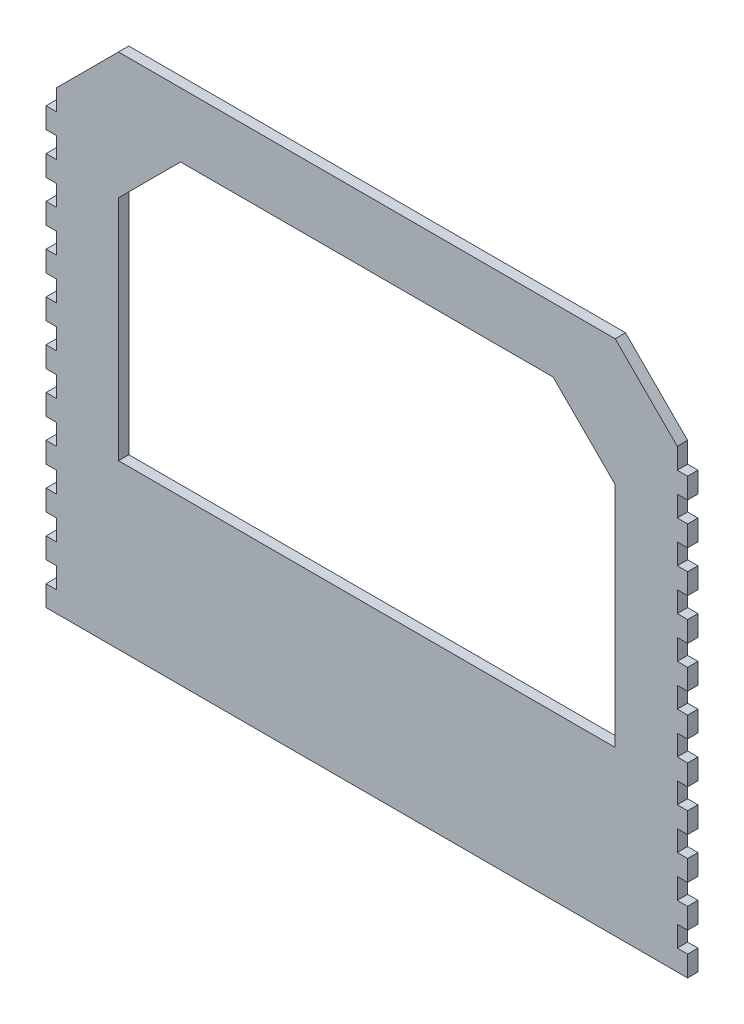
SolidWorks part; units mm, degrees
material "Buche"
ref_plane "Ebene vorne" through (0, 0, 0) normal (0, 0, 1) x (1, 0, 0)
ref_plane "Ebene oben" through (0, 0, 0) normal (0, 1, 0) x (1, 0, 0)
ref_plane "Ebene rechts" through (0, 0, 0) normal (1, 0, 0) x (0, 0, -1)
sketch "Skizze1" plane through (0, 0, 0) normal (0, 0, 1) x (1, 0, 0)
  line L0 (430.8962, 326.3402) -> (430.8962, 336.3402)
  line L1 (430.8962, 316.3402) -> (730.8962, 316.3402)
  line L2 (730.8962, 326.3402) -> (730.8962, 336.3402)
  line L3 (460.8962, 566.3402) -> (700.8962, 566.3402)
  line L4 (430.8962, 536.3402) -> (460.8962, 566.3402)
  line L5 (730.8962, 536.3402) -> (700.8962, 566.3402)
  line L6 (700.8962, 505.3114) -> (670.8962, 535.3114)
  line L7 (460.8962, 395.3114) -> (700.8962, 395.3114)
  line L8 (460.8962, 395.3114) -> (460.8962, 505.3114)
  line L9 (490.8962, 535.3114) -> (670.8962, 535.3114)
  line L10 (700.8962, 395.3114) -> (700.8962, 505.3114)
  line L11 (460.8962, 505.3114) -> (490.8962, 535.3114)
  line L13 (730.8962, 316.3402) -> (735.8962, 316.3402)
  line L14 (735.8962, 316.3402) -> (735.8962, 326.3402)
  line L15 (735.8962, 326.3402) -> (730.8962, 326.3402)
  line L16 (730.8962, 346.3402) -> (730.8962, 356.3402)
  line L17 (730.8962, 336.3402) -> (735.8962, 336.3402)
  line L18 (735.8962, 336.3402) -> (735.8962, 346.3402)
  line L19 (735.8962, 346.3402) -> (730.8962, 346.3402)
  line L20 (730.8962, 366.3402) -> (730.8962, 376.3402)
  line L21 (730.8962, 356.3402) -> (735.8962, 356.3402)
  line L22 (735.8962, 356.3402) -> (735.8962, 366.3402)
  line L23 (735.8962, 366.3402) -> (730.8962, 366.3402)
  line L24 (730.8962, 386.3402) -> (730.8962, 396.3402)
  line L25 (730.8962, 376.3402) -> (735.8962, 376.3402)
  line L26 (735.8962, 376.3402) -> (735.8962, 386.3402)
  line L27 (735.8962, 386.3402) -> (730.8962, 386.3402)
  line L28 (730.8962, 406.3402) -> (730.8962, 416.3402)
  line L29 (730.8962, 396.3402) -> (735.8962, 396.3402)
  line L30 (735.8962, 396.3402) -> (735.8962, 406.3402)
  line L31 (735.8962, 406.3402) -> (730.8962, 406.3402)
  line L32 (730.8962, 426.3402) -> (730.8962, 436.3402)
  line L33 (730.8962, 416.3402) -> (735.8962, 416.3402)
  line L34 (735.8962, 416.3402) -> (735.8962, 426.3402)
  line L35 (735.8962, 426.3402) -> (730.8962, 426.3402)
  line L36 (730.8962, 446.3402) -> (730.8962, 456.3402)
  line L37 (730.8962, 436.3402) -> (735.8962, 436.3402)
  line L38 (735.8962, 436.3402) -> (735.8962, 446.3402)
  line L39 (735.8962, 446.3402) -> (730.8962, 446.3402)
  line L40 (730.8962, 466.3402) -> (730.8962, 476.3402)
  line L41 (730.8962, 456.3402) -> (735.8962, 456.3402)
  line L42 (735.8962, 456.3402) -> (735.8962, 466.3402)
  line L43 (735.8962, 466.3402) -> (730.8962, 466.3402)
  line L44 (730.8962, 486.3402) -> (730.8962, 496.3402)
  line L45 (730.8962, 476.3402) -> (735.8962, 476.3402)
  line L46 (735.8962, 476.3402) -> (735.8962, 486.3402)
  line L47 (735.8962, 486.3402) -> (730.8962, 486.3402)
  line L48 (730.8962, 506.3402) -> (730.8962, 516.3402)
  line L49 (730.8962, 496.3402) -> (735.8962, 496.3402)
  line L50 (735.8962, 496.3402) -> (735.8962, 506.3402)
  line L51 (735.8962, 506.3402) -> (730.8962, 506.3402)
  line L52 (730.8962, 526.3402) -> (730.8962, 536.3402)
  line L53 (730.8962, 516.3402) -> (735.8962, 516.3402)
  line L54 (735.8962, 516.3402) -> (735.8962, 526.3402)
  line L55 (735.8962, 526.3402) -> (730.8962, 526.3402)
  line L56 (430.8962, 316.3402) -> (425.8962, 316.3402)
  line L57 (425.8962, 316.3402) -> (425.8962, 326.3402)
  line L58 (425.8962, 326.3402) -> (430.8962, 326.3402)
  line L59 (430.8962, 346.3402) -> (430.8962, 356.3402)
  line L60 (425.8962, 336.3402) -> (425.8962, 346.3402)
  line L61 (425.8962, 346.3402) -> (430.8962, 346.3402)
  line L62 (430.8962, 366.3402) -> (430.8962, 376.3402)
  line L63 (425.8962, 356.3402) -> (425.8962, 366.3402)
  line L64 (425.8962, 366.3402) -> (430.8962, 366.3402)
  line L65 (430.8962, 386.3402) -> (430.8962, 396.3402)
  line L66 (425.8962, 376.3402) -> (425.8962, 386.3402)
  line L67 (425.8962, 386.3402) -> (430.8962, 386.3402)
  line L68 (430.8962, 406.3402) -> (430.8962, 416.3402)
  line L69 (425.8962, 396.3402) -> (425.8962, 406.3402)
  line L70 (425.8962, 406.3402) -> (430.8962, 406.3402)
  line L71 (430.8962, 426.3402) -> (430.8962, 436.3402)
  line L72 (425.8962, 416.3402) -> (425.8962, 426.3402)
  line L73 (425.8962, 426.3402) -> (430.8962, 426.3402)
  line L74 (430.8962, 446.3402) -> (430.8962, 456.3402)
  line L75 (425.8962, 436.3402) -> (425.8962, 446.3402)
  line L76 (425.8962, 446.3402) -> (430.8962, 446.3402)
  line L77 (430.8962, 466.3402) -> (430.8962, 476.3402)
  line L78 (425.8962, 456.3402) -> (425.8962, 466.3402)
  line L79 (425.8962, 466.3402) -> (430.8962, 466.3402)
  line L80 (430.8962, 486.3402) -> (430.8962, 496.3402)
  line L81 (425.8962, 476.3402) -> (425.8962, 486.3402)
  line L82 (425.8962, 486.3402) -> (430.8962, 486.3402)
  line L83 (430.8962, 506.3402) -> (430.8962, 516.3402)
  line L84 (425.8962, 496.3402) -> (425.8962, 506.3402)
  line L85 (425.8962, 506.3402) -> (430.8962, 506.3402)
  line L86 (430.8962, 526.3402) -> (430.8962, 536.3402)
  line L87 (425.8962, 516.3402) -> (425.8962, 526.3402)
  line L88 (425.8962, 526.3402) -> (430.8962, 526.3402)
  line L89 (425.8962, 336.3402) -> (430.8962, 336.3402)
  line L90 (425.8962, 356.3402) -> (430.8962, 356.3402)
  line L91 (425.8962, 376.3402) -> (430.8962, 376.3402)
  line L92 (425.8962, 396.3402) -> (430.8962, 396.3402)
  line L93 (425.8962, 416.3402) -> (430.8962, 416.3402)
  line L94 (425.8962, 436.3402) -> (430.8962, 436.3402)
  line L95 (425.8962, 456.3402) -> (430.8962, 456.3402)
  line L96 (425.8962, 476.3402) -> (430.8962, 476.3402)
  line L97 (425.8962, 496.3402) -> (430.8962, 496.3402)
  line L98 (425.8962, 516.3402) -> (430.8962, 516.3402)
extrude "Aufsatz-Linear austragen1" add sketch "Skizze1" along normal blind 5
